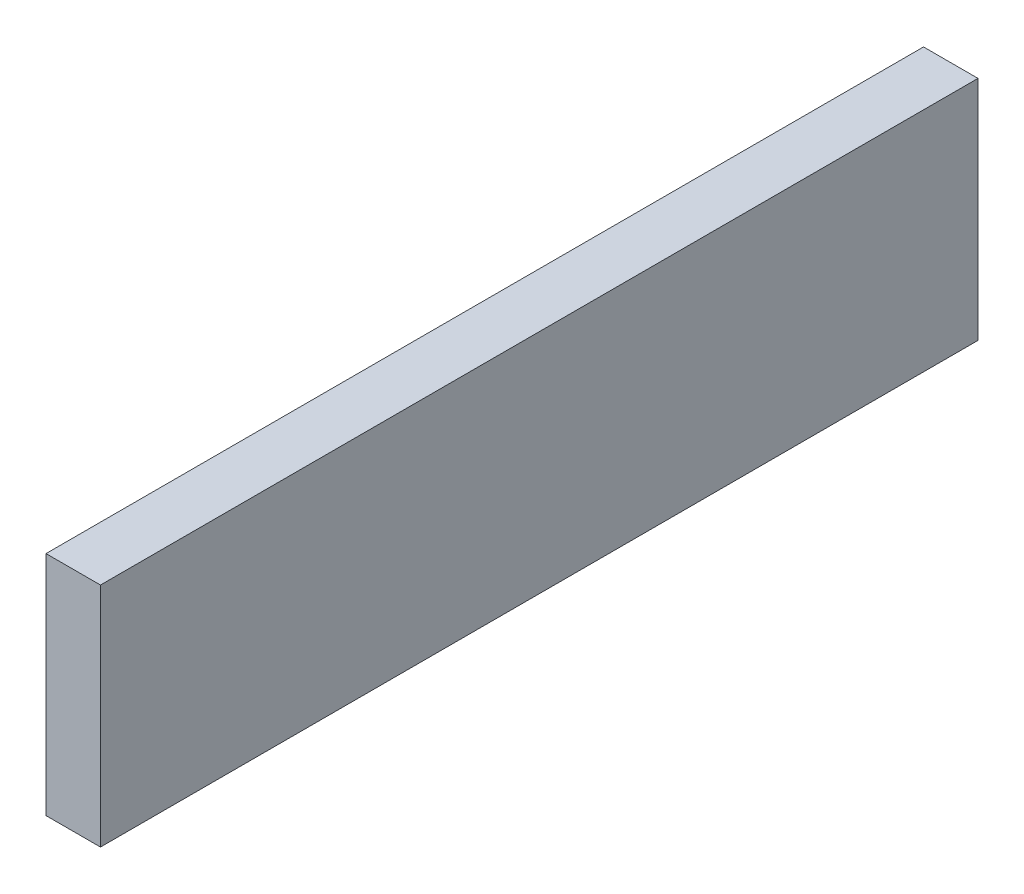
SolidWorks part; units mm, degrees
material "Mahogany"
ref_plane "Front Plane" through (0, 0, 0) normal (0, 0, 1) x (1, 0, 0)
ref_plane "Top Plane" through (0, 0, 0) normal (0, 1, 0) x (1, 0, 0)
ref_plane "Right Plane" through (0, 0, 0) normal (1, 0, 0) x (0, 0, -1)
sketch "Sketch1" plane through (0, 0, 0) normal (1, 0, 0) x (0, 0, -1)
  line L1 (-145, -37.5) -> (145, -37.5)
  line L2 (-145, -37.5) -> (-145, 37.5)
  line L3 (-145, 37.5) -> (145, 37.5)
  line L4 (145, -37.5) -> (145, 37.5)
  line L5 (-145, -37.5) -> (145, 37.5) construction
  line L6 (-145, 37.5) -> (145, -37.5) construction
  point P0 (0, 0)
  dimension "D1" = 290
  dimension "D2" = 75
extrude "Boss-Extrude1" add sketch "Sketch1" along normal mid plane 18
